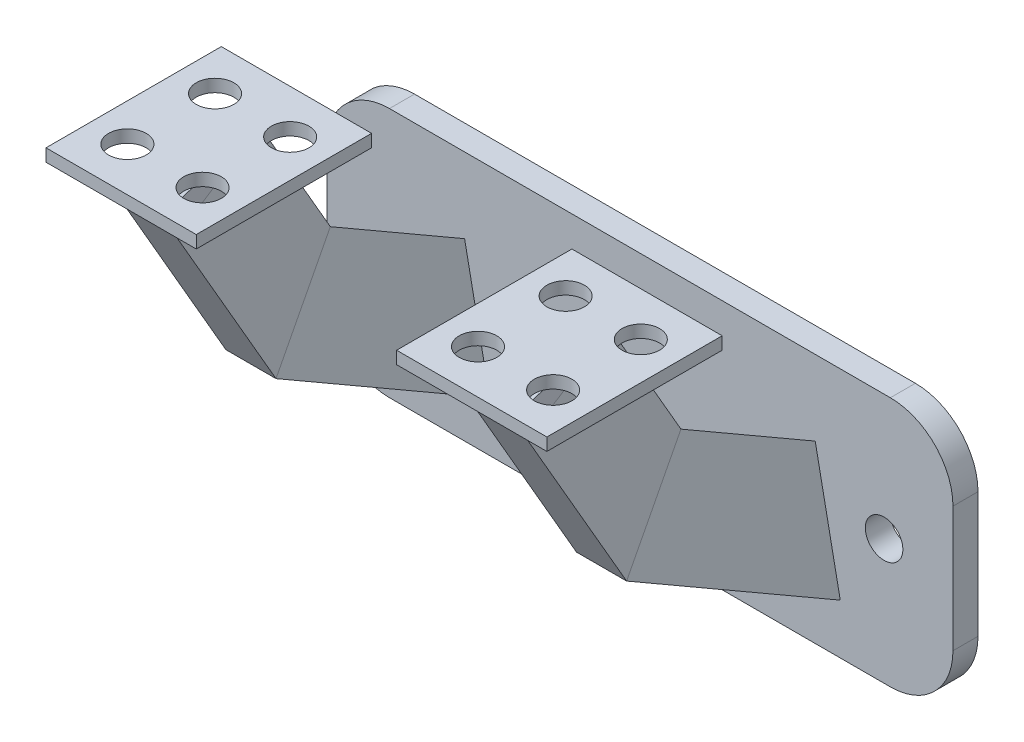
SolidWorks part; units mm, degrees
ref_plane "前视基准面" through (0, 0, 0) normal (0, 0, 1) x (1, 0, 0)
ref_plane "上视基准面" through (0, 0, 0) normal (0, 1, 0) x (1, 0, 0)
ref_plane "右视基准面" through (0, 0, 0) normal (1, 0, 0) x (0, 0, -1)
sketch "草图1" plane through (0, 0, 0) normal (0, 0, 1) x (1, 0, 0)
  line L1 (-25, 10) -> (25, 10)
  line L2 (-25, 10) -> (-25, -10)
  line L3 (-25, -10) -> (25, -10)
  line L4 (25, 10) -> (25, -10)
  line L5 (0, -10) -> (0, 10) construction
  line L6 (-25, 0) -> (25, 0) construction
  circle A0 centre (-19.5, 0) radius 1.5
  circle A1 centre (19.5, 0) radius 1.5
  point P0 (0, 0)
  dimension "D3" = 3
  dimension "D4" = 19.5
  dimension "D5" = 39
  dimension "D1" = 50
  dimension "D2" = 20
extrude "凸台-拉伸1" add sketch "草图1" along normal blind 2
fillet "圆角1" radius 5 4 edges at (25, 10, 1) (25, -10, 1) (-25, -10, 1) (-25, 10, 1)
sketch "草图2" plane through (0, 0, 2) normal (0, 0, 1) x (1, 0, 0)
  line L0 (14, 4) -> (12, -6)
  line L1 (12, -6) -> (16, -6)
  line L2 (16, -6) -> (14, 4)
  circle A0 centre (14, -4.3604) radius 1.6396 construction
  point P7 (14, -4.3604)
  dimension "D1" = 10
  dimension "D2" = 4
  dimension "D3" = 12
  dimension "D4" = 6
ref_plane "基准面1" through (0, 20, 0) normal (0, 1, 0) x (1, 0, 0)
ref_plane "基准面2" through (14, 0, 0) normal (1, 0, 0) x (0, 0, -1)
sketch "草图6" plane through (14, 0, 0) normal (1, 0, 0) x (0, 0, -1)
  line L0 (-2, -4.3604) -> (-18.022, 4.8899)
  line L1 (-18.022, 4.8899) -> (-25.5911, 18)
  line L2 (-2, -4.3604) -> (-14.4661, -4.3604) construction
  line L3 (-25.5911, 18) -> (-25.5911, 22)
  point P7 (-26.2366, 18.0332)
  dimension "D1" = 18
  dimension "D2" = 30
  dimension "D3" = 150
  dimension "D4" = 4
sweep "扫描1" add profiles "草图2" path "草图6"
sketch "草图7" plane through (0, 20, 0) normal (0, 1, 0) x (1, 0, 0)
  line L0 (14, -14.8561) -> (14, 14.8561) construction
  line L1 (12, -9.6905) -> (16, -9.6905)
  line L2 (12, -9.6905) -> (12, -27.011)
  line L3 (12, -27.011) -> (16, -27.011)
  line L4 (16, -9.6905) -> (16, -27.011)
  line L5 (14, -27.011) -> (14, -9.6905) construction
  line L6 (12, -18.3508) -> (16, -18.3508) construction
  line L7 (16, -27.011) -> (14, -18.3508) construction
  point P0 (14, -18.3508)
extrude "切除-拉伸1" cut sketch "草图7" along normal blind 8
sketch "草图9" plane through (0, 20, 0) normal (0, 1, 0) x (1, 0, 0)
  line L1 (8, -15.4294) -> (20, -15.4294)
  line L2 (8, -15.4294) -> (8, -29.4294)
  line L3 (8, -29.4294) -> (20, -29.4294)
  line L4 (20, -15.4294) -> (20, -29.4294)
  line L5 (14, -29.4294) -> (14, -15.4294) construction
  line L6 (8, -22.4294) -> (20, -22.4294) construction
  point P0 (14, -22.4294)
  dimension "D1" = 14
  dimension "D2" = 12
extrude "凸台-拉伸3" add sketch "草图9" along normal blind 1
sketch "草图10" plane through (0, 21, 0) normal (0, 1, 0) x (1, 0, 0)
  line L0 (8, -15.4294) -> (20, -29.4294) construction
  line L1 (20, -15.4294) -> (8, -29.4294) construction
  line L2 (20, -15.4294) -> (8, -15.4294) construction
  line L4 (8, -29.4294) -> (20, -29.4294) construction
  circle A0 centre (11, -25.9294) radius 1.5
  circle A1 centre (17, -18.9294) radius 1.5
  circle A2 centre (11, -18.9294) radius 1.5
  circle A3 centre (17, -25.9294) radius 1.5
  dimension "D1" = 3
  dimension "D3" = 3.5
  dimension "D4" = 3.5
  dimension "D5" = 3.5
  dimension "D2" = 3.5
extrude "切除-拉伸2" cut sketch "草图10" against normal blind 1
mirror "镜向1" about plane through (0, 0, 0) normal (1, 0, 0) of "扫描1", "切除-拉伸1", "凸台-拉伸3", "切除-拉伸2"
